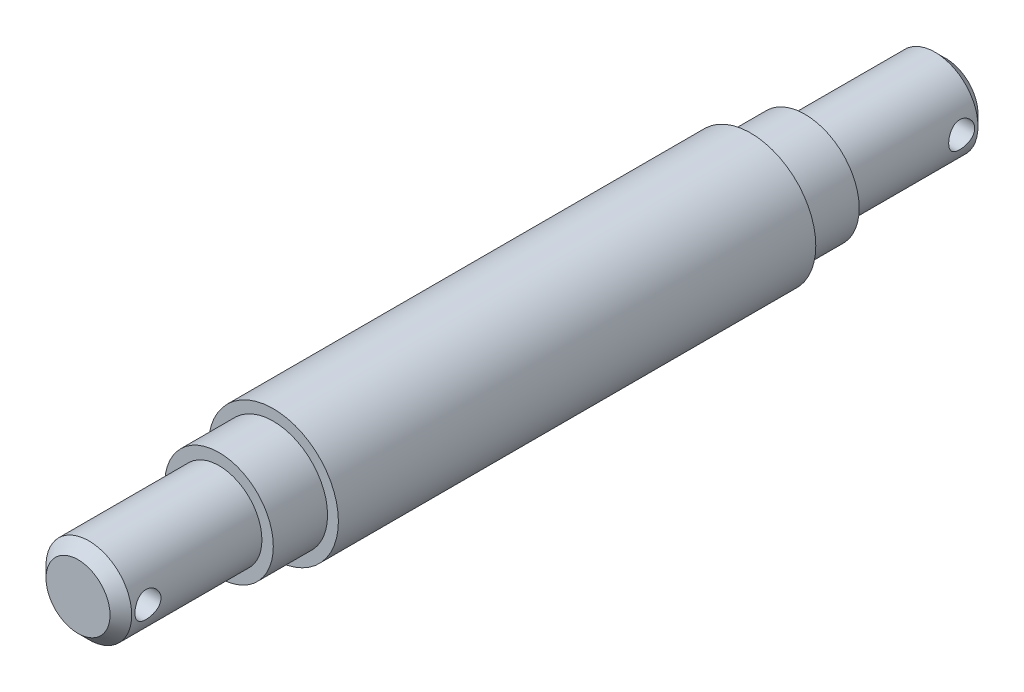
SolidWorks part; units mm, degrees
material "Mahogany"
ref_plane "Front Plane" through (0, 0, 0) normal (0, 0, 1) x (1, 0, 0)
ref_plane "Top Plane" through (0, 0, 0) normal (0, 1, 0) x (1, 0, 0)
ref_plane "Right Plane" through (0, 0, 0) normal (1, 0, 0) x (0, 0, -1)
sketch "Sketch1" plane through (0, 0, 0) normal (0, 0, 1) x (1, 0, 0)
  circle A0 centre (0, 0) radius 6
  dimension "D1" = 12
extrude "Boss-Extrude1" add sketch "Sketch1" along normal mid plane 44
sketch "Sketch2" plane through (0, 0, 22) normal (0, 0, 1) x (1, 0, 0)
  circle A0 centre (0, 0) radius 5
  dimension "D1" = 10
extrude "Boss-Extrude2" add sketch "Sketch2" along normal blind 5
sketch "Sketch3" plane through (0, 0, 27) normal (0, 0, 1) x (1, 0, 0)
  circle A0 centre (0, 0) radius 3.95
  dimension "D1" = 7.9
extrude "Boss-Extrude3" add sketch "Sketch3" along normal blind 13
sketch "Sketch4" plane through (0, 0, 0) normal (1, 0, 0) x (0, 0, -1)
  line L0 (-40, 3.95) -> (-40, -3.95) construction
  line L1 (-40, 3.95) -> (-40, -3.95)
  circle A0 centre (-37.5, 0) radius 1.2
extrude "Cut-Extrude1" cut sketch "Sketch4" against normal mid plane 13 contours A0
chamfer "Chamfer1" distance 1 angle 45 1 edges at (3.95, 0, 40)
mirror "Mirror1" about plane through (0, 0, 0) normal (0, 0, 1) of "Boss-Extrude3", "Boss-Extrude2"
mirror "Mirror2" about plane through (0, 0, 0) normal (0, 0, 1) of "Cut-Extrude1"
chamfer "Chamfer2" distance 1 angle 45 1 edges at (3.95, 0, -40)
